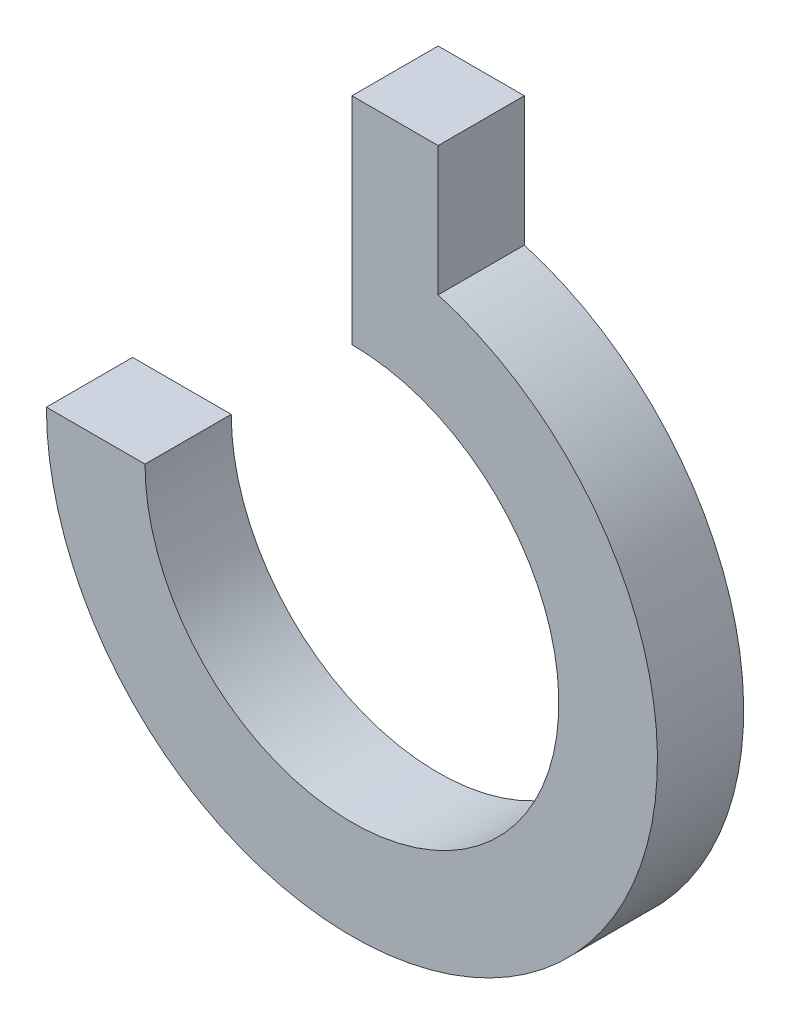
SolidWorks part; units mm, degrees
material "Alloy Steel (SS)"
ref_plane "Front Plane" through (0, 0, 0) normal (0, 0, 1) x (1, 0, 0)
ref_plane "Top Plane" through (0, 0, 0) normal (0, 1, 0) x (1, 0, 0)
ref_plane "Right Plane" through (0, 0, 0) normal (1, 0, 0) x (0, 0, -1)
sketch "Sketch1" plane through (0, 0, 0) normal (0, 0, 1) x (1, 0, 0)
  line L0 (0, 62.5) -> (0, -62.5)
  line L1 (0, 62.5) -> (50, 62.5)
  line L2 (50, 62.5) -> (50, -12.5)
  line L3 (-120, -182.5) -> (-177.2005, -182.5)
  arc A0 (-120, -182.5) -> (0, -62.5) centre (0, -182.5) ccw
  arc A1 (-177.2005, -182.5) -> (50, -12.5) centre (0, -182.5) ccw
  point P4 (0, 0)
  point P8 (0, 0)
  point P9 (0, 0)
  dimension "D1" = 125
  dimension "D4" = 120
  dimension "D2" = 50
  dimension "D3" = 75
extrude "Boss-Extrude1" add sketch "Sketch1" along normal blind 50
